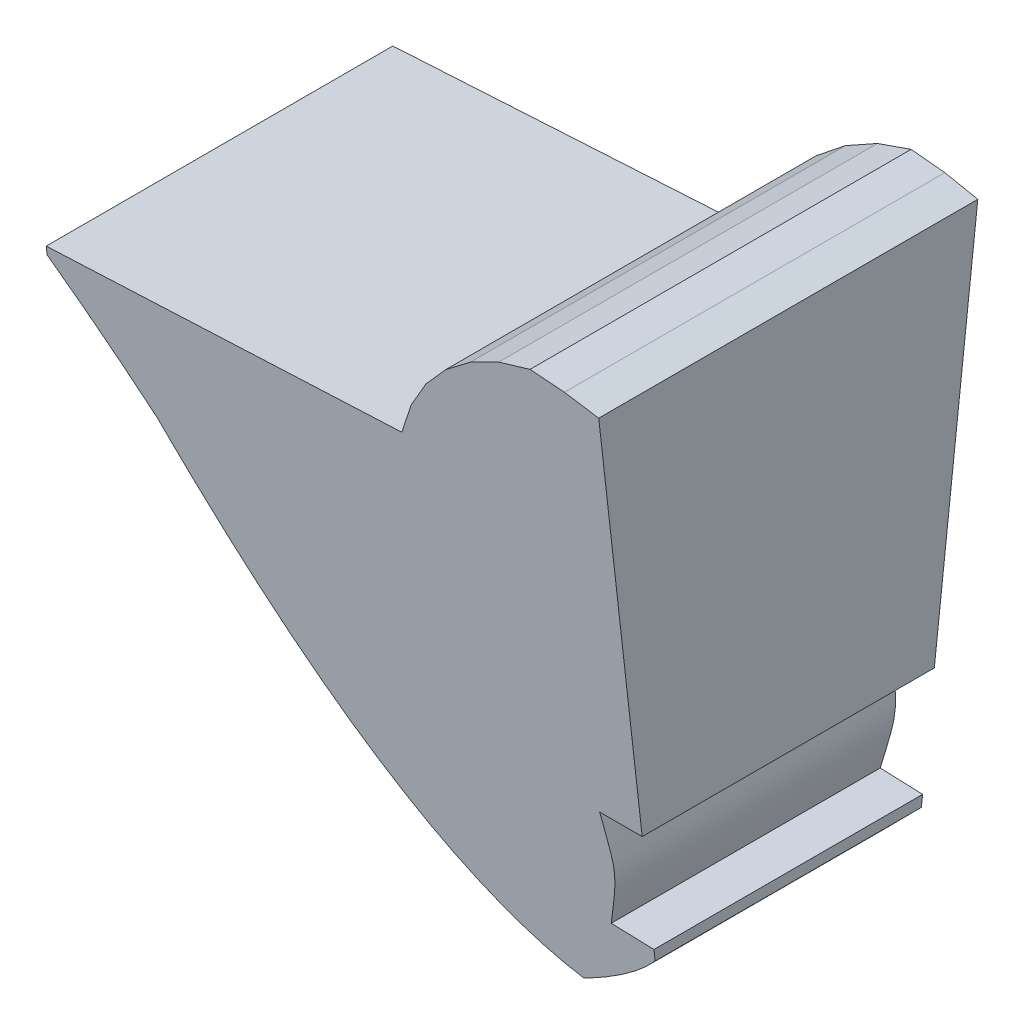
SolidWorks part; units mm, degrees
ref_plane "Alzado" through (0, 0, 0) normal (0, 0, 1) x (1, 0, 0)
ref_plane "Planta" through (0, 0, 0) normal (0, 1, 0) x (1, 0, 0)
ref_plane "Vista lateral" through (0, 0, 0) normal (1, 0, 0) x (0, 0, -1)
sketch "Croquis1" plane through (0, 0, 0) normal (0, 0, 1) x (1, 0, 0)
  line L0 (-8.9818, 12.6082) -> (-23.0359, 11.8716) construction
  line L1 (-8.9818, 12.6082) -> (-23.0359, 11.8716)
  line L2 (-8.9818, 12.6082) -> (-23.0359, 11.8716) construction
  line L4 (-8.9818, 12.6082) -> (-23.0359, 11.8716)
  line L6 (-1.3949, 1.9763) -> (0.3551, 2.2848) construction
  line L7 (-1.3949, 1.9763) -> (0.3551, 2.2848)
  line L8 (0.3551, 2.2848) -> (0.3551, 2.8423) construction
  line L9 (0.3551, 2.2848) -> (0.3551, 3.0015)
  line L10 (0.3551, -2.2848) -> (-1.3949, -2.2237) construction
  line L11 (0.3551, -2.2848) -> (-1.3949, -2.2237)
  line L12 (0.3551, 2.2848) -> (0.3551, -2.2848) construction
  line L13 (0.3551, -2.2848) -> (0.3551, -2.7233)
  line L14 (-8.9818, 12.6082) -> (-6.9949, 10.4774)
  line L15 (-23.0359, 11.5401) -> (-23.0359, 11.8716) construction
  line L16 (-23.0359, 11.5401) -> (-23.0359, 11.8716)
  arc A0 (-18.9452, 7.5409) -> (-23.0359, 11.5401) centre (-69.8841, -40.4718) ccw construction
  arc A1 (-18.9452, 7.5409) -> (-23.0359, 11.5401) centre (-69.8841, -40.4718) ccw
  spline S1 degree 2 poles (-828.7061, 3922.2202) (545.889, -3962.7836) (-262.0834, 3982.5902) knots 0.462185 0.462185 0.462185 0.537731 0.537731 0.537731 weights 1 1 1 only from (-18.9452, 7.5409) to (-2.8466, -5.0591) construction
  spline S2 degree 2 poles (-18.9452, 7.5409) (-10.215, -3.6976) (-2.8466, -5.0591) knots 0.497667 0.497667 0.497667 0.499554 0.499554 0.499554 weights 1 1 1
  spline S3 degree 2 poles (-3804.8689, 1232.5771) (3762.9122, -1369.6643) (-3716.5752, 1504.852) knots 0.462212 0.462212 0.462212 0.537836 0.537836 0.537836 weights 1 1 1 only from (0.3551, 3.0015) to (-6.9949, 10.4774) construction
  spline S4 degree 2 poles (0.3551, 3.0015) (-1.4487, 6.0584) (-6.9949, 10.4774) knots 0.500821 0.500821 0.500821 0.502013 0.502013 0.502013 weights 1 1 1
  spline S5 degree 2 poles (-1.3949, -2.2237) (-0.9075, -0.1237) (-1.3949, 1.9763) knots 0 0 0 1 1 1 weights 1 3.231801 1 construction
  spline S6 degree 2 poles (-1.3949, -2.2237) (-0.9075, -0.1237) (-1.3949, 1.9763) knots 0 0 0 1 1 1 weights 1 3.231801 1
  spline S7 degree 2 poles (-3997.263, 185.0077) (3984.2333, -348.7483) (-3965.0625, 511.2595) knots 0.462205 0.462205 0.462205 0.537778 0.537778 0.537778 weights 1 1 1 only from (-2.8466, -5.0591) to (0.3551, -2.7233) construction
  spline S8 degree 2 poles (-2.8466, -5.0591) (-0.7424, -3.9352) (0.3551, -2.7233) knots 0.498812 0.498812 0.498812 0.499413 0.499413 0.499413 weights 1 1 1
extrude "Saliente-Extruir1" add sketch "Croquis1" along normal mid plane 14.42 contours S2 S8 L13 L11 S6 L7 L9 S4 L14 L1 L16 A1
sketch "Croquis3" plane through (0, 0, 0) normal (0, 0, 1) x (1, 0, 0)
  line L0 (-6.742, 0) -> (0, 0) construction
  line L1 (-1.8181, 2) -> (-1.7771, 2.0103) construction
  line L3 (-1.8181, 2) -> (-0.1689, 2.4155) construction
  line L4 (-1.8181, 2) -> (0.3551, 3.0015)
  line L5 (0.3551, 3.0015) -> (0.3551, 0)
  line L6 (-1.9112, -2.1782) -> (0.3551, -2.2848)
  line L7 (0.3551, -2.2848) -> (0.3551, 0)
  parabola Q0 (-1.9112, -2.1782) -> (-1.8181, 2) focus (-3.3181, 0) apex (-1.3181, 0)
  dimension "D1" = 2
  dimension "D2" = 2
extrude "Cortar-Extruir1" [suppressed] cut sketch "Croquis3" against normal through all both and the other way through all
sketch "Croquis4" plane through (0, 0, 0) normal (0, 0, 1) x (1, 0, 0)
  line L0 (-1.3949, 1.9763) -> (0.3551, 2.2848) construction
  line L1 (-1.3949, 1.9763) -> (0.3551, 2.2848)
  line L2 (0.3551, 2.2848) -> (0.3551, 3.0015) construction
  line L3 (0.3551, 1.9763) -> (0.3551, 2.2848)
  line L4 (-1.3949, 1.9763) -> (0.3551, 1.9763)
  line L5 (0, 0) -> (-3.4665, 0) construction
  dimension "D1" = 0
extrude "Saliente-Extruir2" add sketch "Croquis4" along normal through all and the other way through all
sketch "Croquis7" plane through (0, 0, 0) normal (0, 0, 1) x (1, 0, 0)
  line L0 (0, 0) -> (-13.2475, 1.1183) construction
  line L1 (-14.9286, 14.3063) -> (-13.2475, 1.1183) construction
  line L2 (-13.2475, 1.1183) -> (-7.4174, -4.4688) construction
  line L3 (-13.2475, 1.1183) -> (-8.4034, 6.1732) construction
  line L4 (-14.9286, 14.3063) -> (-14.7, 12.5132) construction
  line L5 (0, 0) -> (-1.3461, -2.2254) construction
  line L6 (-69.8841, 29.5282) -> (-81.9382, 42.5765) construction
  line L7 (-69.8841, 29.5282) -> (-20.9497, 29.5282) construction
  line L8 (-17.8101, 13.1658) -> (-25.5429, 13.1658)
  line L9 (-17.6007, 6.3083) -> (-21.9246, 11.9299) construction
  line L10 (0.3551, -2.5) -> (-2.4497, -2.0473)
  line L11 (-1.3461, -2.2254) -> (-2.0075, -3.6222) construction
  line L12 (-1.3461, -2.2254) -> (-1.4547, -2.8987) construction
  line L13 (-1.3461, -2.2254) -> (-1.2286, -1.4976) construction
  line L14 (0.3551, -2.2848) -> (0.3551, -2.7233) construction
  line L15 (0.3551, -2.2848) -> (-1.3949, -2.2237) construction
  line L16 (-2.0075, -3.6222) -> (-2.6381, -4.9541) construction
  line L17 (-2.6331, -4.9434) -> (-3.7044, -5.5324) construction
  line L18 (-2.6331, -4.9434) -> (-3.2248, -3.867) construction
  line L19 (-2.6331, -4.9434) -> (-2.2174, -6.1341) construction
  line L20 (-4.0838, -4.7637) -> (-2.6213, -4.9448) construction
  line L21 (-4.0838, -4.7637) -> (-0.036, -5.9454) construction
  line L22 (-4.0838, -4.7637) -> (-3.7621, -3.6616) construction
  line L23 (-4.0838, -4.7637) -> (-5.4141, -4.1295) construction
  line L24 (-5.4141, -4.1295) -> (-8.69, -2.5677) construction
  line L25 (-8.69, -2.5677) -> (-6.8421, -3.7725) construction
  line L26 (-8.69, -2.5677) -> (-7.9481, -1.4297) construction
  line L27 (-11.4407, -0.2002) -> (-8.69, -2.5677) construction
  line L28 (-11.4407, -0.2002) -> (-14.8546, 2.738) construction
  line L29 (-14.8546, 2.738) -> (-14.5337, 2.3989) construction
  line L30 (-14.8546, 2.738) -> (-14.6199, 2.9602) construction
  line L31 (-17.6007, 6.3083) -> (-14.8546, 2.738) construction
  line L32 (-8.9818, 12.6082) -> (-23.0359, 11.8716) construction
  line L33 (-8.9818, 12.6082) -> (-23.0359, 11.8716)
  line L34 (-21.9246, 11.9299) -> (-21.9826, 13.0367) construction
  line L35 (-21.9246, 11.9299) -> (-23.4156, 13.0367) construction
  arc A0 (-18.9452, 7.5409) -> (-23.0359, 11.5401) centre (-69.8841, -40.4718) ccw construction
  spline S0 degree 2 poles (-828.7061, 3922.2202) (545.889, -3962.7836) (-262.0834, 3982.5902) knots 0.462185 0.462185 0.462185 0.537731 0.537731 0.537731 weights 1 1 1 only from (-18.9452, 7.5409) to (-2.8466, -5.0591) construction
  spline S1 degree 2 poles (-18.6263, 7.1332) (-10.0803, -3.7225) (-2.8466, -5.0591) knots 0.497702 0.497702 0.497702 0.499554 0.499554 0.499554 weights 1 1 1 construction
  spline S3 degree 2 poles (-3997.263, 185.0077) (3984.2333, -348.7483) (-3965.0625, 511.2595) knots 0.462205 0.462205 0.462205 0.537778 0.537778 0.537778 weights 1 1 1 only from (-2.8466, -5.0591) to (0.3551, -2.7233) construction
  spline S4 degree 2 poles (-2.8466, -5.0591) (-2.7385, -5.0013) (-2.6331, -4.9434) knots 0.498812 0.498812 0.498812 0.498843 0.498843 0.498843 weights 1 1 1
  dimension "D1" = 2.5
  dimension "D2" = 22
  dimension "D3" = 16.17
  dimension "D4" = 54.138
  dimension "D5" = 34.566
  dimension "D6" = 50.413
sketch "Croquis6" plane through (0, 0, 0) normal (1, 0, 0) x (0, 0, -1)
  line L0 (7.21, 12.6082) -> (7.21, 10.4774) construction
  line L1 (7.21, 12.6082) -> (7.21, -5.0591)
  line L2 (-7.21, 12.6082) -> (-7.21, 10.4774) construction
  line L3 (-7.21, 12.6082) -> (-7.21, -5.0591)
  line L4 (-7.21, -5.0591) -> (7.21, -5.0591) construction
  line L5 (-7.21, -5.0591) -> (-5.21, -5.0591)
  line L6 (7.21, 12.6082) -> (5.21, -5.0591)
  line L7 (-7.21, 12.6082) -> (-5.21, -5.0591)
  line L8 (5.21, -5.0591) -> (7.21, -5.0591)
  dimension "D1" = 2
  dimension "D2" = 2
extrude "Cortar-Extruir2" cut sketch "Croquis6" against normal through all and the other way through all
sketch "Croquis8" plane through (0, 0, 0) normal (0, 0, 1) x (1, 0, 0)
  line L0 (-8.9818, 12.6082) -> (-23.0359, 11.8716) construction
  line L1 (-9.7264, 12.5691) -> (0.3551, 17.7735) construction
  line L2 (0.3551, 1.9763) -> (0.3551, 3.0015) construction
  line L3 (0.3551, 3.0015) -> (0.3551, 17.7735)
  line L5 (-8.3233, 12.6427) -> (-7.797, 13.9454)
  line L6 (-7.797, 13.9454) -> (-7.0524, 15.1369)
  line L7 (-7.0524, 15.1369) -> (-6.1123, 16.1811)
  line L8 (-6.1123, 16.1811) -> (-5.0051, 17.0461)
  line L9 (-5.0051, 17.0461) -> (-3.7645, 17.7057)
  line L10 (-3.7645, 17.7057) -> (-2.4283, 18.1399)
  line L11 (-2.4283, 18.1399) -> (-1.0286, 18.0174)
  line L12 (-1.0286, 18.0174) -> (0.3551, 17.7735)
  line L13 (-0.5199, 1.9763) -> (-9.282, 12.9915) construction
  line L14 (-9.282, 12.9915) -> (-9.6919, 13.4229) construction
  line L15 (-9.282, 12.9915) -> (-9.8512, 13.838) construction
  line L16 (-0.5199, 1.9763) -> (-8.0602, 13.294) construction
  line L17 (-8.0602, 13.294) -> (-9.1208, 13.7226) construction
  line L18 (-0.5199, 1.9763) -> (-7.4247, 14.5412) construction
  line L19 (0.3551, 1.9763) -> (-1.3949, 1.9763) construction
  line L20 (-7.4247, 14.5412) -> (-7.564, 14.6282) construction
  line L21 (-0.5199, 1.9763) -> (-6.5824, 15.659) construction
  line L22 (-0.5199, 1.9763) -> (-5.5587, 16.6136) construction
  line L23 (-5.5587, 16.6136) -> (-6.1777, 17.4058) construction
  line L24 (-0.5199, 1.9763) -> (-4.3848, 17.3759) construction
  line L25 (-4.3848, 17.3759) -> (-4.7166, 18) construction
  line L26 (-0.5199, 1.9763) -> (-3.0964, 17.9228) construction
  line L27 (-3.0964, 17.9228) -> (-3.34, 18.6726) construction
  line L28 (-0.5199, 1.9763) -> (-1.7284, 18.0787) construction
  line L29 (-1.7284, 18.0787) -> (-1.7309, 18.0503) construction
  line L30 (-0.5199, 1.9763) -> (-0.3367, 17.8955) construction
  line L31 (-0.3367, 17.8955) -> (-0.4834, 17.0639) construction
  line L32 (-7.4247, 14.5412) -> (-8.2283, 15.0433) construction
  line L33 (-6.5824, 15.659) -> (-7.2613, 16.2703) construction
  line L34 (-9.7264, 12.5691) -> (-9.7264, 19.4167) construction
  line L35 (-0.3367, 17.8955) -> (-0.2962, 18.1254) construction
  line L36 (-9.7264, 12.5691) -> (-8.3233, 12.6427)
  line L37 (-8.0602, 13.294) -> (-8.3005, 14.335) construction
  line L38 (-8.0602, 13.294) -> (-6.9403, 12.8416) construction
  line L39 (-7.4247, 14.5412) -> (-7.8205, 16.2557) construction
  line L40 (-7.4247, 14.5412) -> (-7.159, 14.3751) construction
  line L41 (-6.5824, 15.659) -> (-6.8504, 16.8201) construction
  line L42 (-6.5824, 15.659) -> (-6.1207, 15.2433) construction
  line L43 (-5.5587, 16.6136) -> (-6.0278, 18.6457) construction
  line L44 (-5.5587, 16.6136) -> (-5.0299, 15.9367) construction
  line L45 (-4.3848, 17.3759) -> (-4.8775, 19.5099) construction
  line L46 (-4.3848, 17.3759) -> (-4.0664, 16.7772) construction
  line L47 (-3.0964, 17.9228) -> (-3.5544, 19.9066) construction
  line L48 (-3.0964, 17.9228) -> (-2.7244, 16.7779) construction
  spline S0 degree 2 poles (-1851.9698, 781.7085) (1883.9916, -685.7524) (-1911.5868, 588.043) knots 0.476049 0.476049 0.476049 0.529551 0.529551 0.529551 weights 1 1 1 only from (-6.9949, 10.4774) to (0.3551, 3.0015) construction
  spline S1 degree 2 poles (-9.7264, 12.5691) (-1.8611, 6.7573) (0.3551, 3.0015) knots 0.500548 0.500548 0.500548 0.502013 0.502013 0.502013 weights 1 1 1
  dimension "D1" = 5.039
  dimension "D2" = 95
  dimension "D3" = 15
  dimension "D4" = 25
  dimension "D5" = 80
  dimension "D6" = 45
  dimension "D7" = 35
  dimension "D8" = 5
  dimension "D9" = 100
  dimension "D10" = 55
  dimension "D11" = 34.327
  dimension "D12" = 29.21
  dimension "D13" = 24.103
  dimension "D14" = 19.004
  dimension "D15" = 13.911
extrude "Saliente-Extruir3" add sketch "Croquis8" along normal up to surface and the other way up to surface up to face at (-6.8548, 3.8413, 6.2176) other way up to face at (-6.9269, 3.652, -6.1961)
